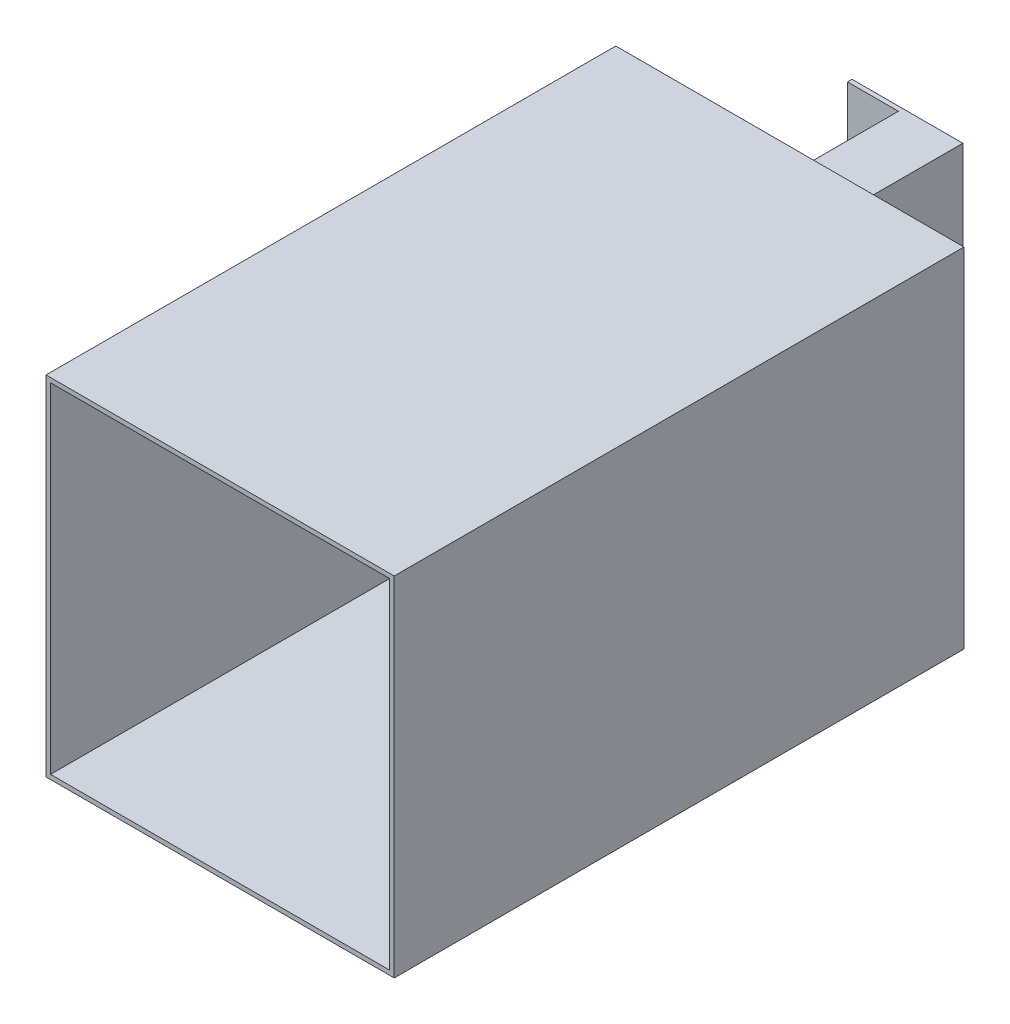
SolidWorks part; units mm, degrees
material "Cast Alloy Steel"
ref_plane "Front Plane" through (0, 0, 0) normal (0, 0, 1) x (1, 0, 0)
ref_plane "Top Plane" through (0, 0, 0) normal (0, 1, 0) x (1, 0, 0)
ref_plane "Right Plane" through (0, 0, 0) normal (1, 0, 0) x (0, 0, -1)
sketch "Sketch1" plane through (0, 0, 0) normal (0, 0, 1) x (1, 0, 0)
  line L0 (-77, 77) -> (77, 77)
  line L1 (-75, 75) -> (75, 75)
  line L2 (-75, 75) -> (-75, -75)
  line L3 (-75, -75) -> (75, -75)
  line L4 (75, 75) -> (75, -75)
  line L5 (-75, 75) -> (75, -75) construction
  line L6 (-75, -75) -> (75, 75) construction
  line L7 (77, 77) -> (77, -77)
  line L8 (-77, -77) -> (77, -77)
  line L9 (-77, 77) -> (-77, -77)
  point P0 (0, 0)
  dimension "D1" = 150
  dimension "D2" = 2
extrude "Boss-Extrude1" add sketch "Sketch1" along normal blind 250
sketch "Sketch2" plane through (0, 0, 0) normal (0, 0, -1) x (-1, 0, 0)
  line L0 (0, 75) -> (0, -75) construction
  line L1 (-77, 77) -> (77, 77)
  line L2 (-77, 77) -> (-77, -77)
  line L3 (-77, -77) -> (77, -77)
  line L4 (77, 77) -> (77, -77)
  line L5 (-75, 75) -> (75, 75) construction
  line L6 (75, -75) -> (-75, -75) construction
  circle A0 centre (0, 40) radius 20
  circle A1 centre (0, 0) radius 4
  dimension "D1" = 40
  dimension "D3" = 8
  dimension "D2" = 35
extrude "Boss-Extrude2" add sketch "Sketch2" along normal blind 2
sketch "Sketch3" plane through (0, 0, -2) normal (0, 0, -1) x (-1, 0, 0)
  line L0 (2, 64.5) -> (2, 62.5)
  line L1 (2, 62.5) -> (0, 62.5)
  line L2 (-22.5, 62.5) -> (-22.5, 17.5)
  line L3 (-22.5, 17.5) -> (22.5, 17.5) construction
  line L4 (22.5, 62.5) -> (22.5, 17.5) construction
  line L7 (-22.5, 62.5) -> (0, 62.5)
  line L8 (-22.5, 17.5) -> (0, 17.5)
  line L10 (-24.5, 15.5) -> (2, 15.5)
  line L11 (-24.5, 64.5) -> (-24.5, 15.5)
  line L12 (-24.5, 64.5) -> (2, 64.5)
  line L14 (2, 64.5) -> (2, 15.5) construction
  line L15 (0, 62.5) -> (0, 17.5) construction
  line L18 (0, 17.5) -> (2, 17.5)
  line L19 (2, 17.5) -> (2, 15.5)
  point P0 (0, 40)
  dimension "D1" = 45
  dimension "D2" = 2
extrude "Boss-Extrude3" add sketch "Sketch3" along normal blind 50
sketch "Sketch4" plane through (0, 0, -52) normal (0, 0, -1) x (-1, 0, 0)
  line L1 (-24.5, 64.5) -> (24.5, 64.5)
  line L2 (-24.5, 64.5) -> (-24.5, 15.5)
  line L3 (-24.5, 15.5) -> (24.5, 15.5)
  line L4 (24.5, 64.5) -> (24.5, 15.5)
  dimension "D1" = 49
  dimension "D2" = 49
extrude "Boss-Extrude4" add sketch "Sketch4" along normal blind 2
sketch "Sketch5" plane through (24.5, 0, 0) normal (1, 0, 0) x (0, 0, -1)
  line L0 (2, 17.5) -> (6, 17.5)
  line L2 (2, 62.5) -> (2, 17.5)
  line L3 (2, 62.5) -> (6, 62.5)
  line L4 (6, 62.5) -> (6, 17.5)
extrude "Cut-Extrude1" cut sketch "Sketch5" against normal blind 2
sketch "Sketch6" plane through (24.5, 0, 0) normal (1, 0, 0) x (0, 0, -1)
  line L1 (54, 40) -> (11.6739, 40) construction
  line L2 (54, 64.5) -> (54, 15.5) construction
  circle A0 centre (32, 40) radius 4
  dimension "D1" = 8
  dimension "D2" = 22
extrude "Cut-Extrude2" cut sketch "Sketch6" against normal blind 70
sketch "Sketch9" plane through (0, 0, 0) normal (0, 0, 1) x (1, 0, 0)
  circle A0 centre (0, 0) radius 74
  circle A1 centre (0, 0) radius 72
  dimension "D1" = 148
  dimension "D2" = 2
extrude "Boss-Extrude9" add sketch "Sketch9" along normal blind 50
sketch "Sketch10" plane through (0, 0, 50) normal (0, 0, 1) x (1, 0, 0)
  circle A0 centre (0, 0) radius 74
ref_plane "Plane1" through (0, 0, 80) normal (0, 0, 1) x (1, 0, 0)
sketch "Sketch12" plane through (0, 0, 80) normal (0, 0, 1) x (1, 0, 0)
  line L1 (-75, 75) -> (75, 75)
  line L2 (-75, 75) -> (-75, -75)
  line L3 (-75, -75) -> (75, -75)
  line L4 (75, 75) -> (75, -75)
sketch "Sketch13" plane through (0, 0, 0) normal (0, 1, 0) x (1, 0, 0)
  line L0 (74, -50) -> (75, -80)
  line L1 (-74, -50) -> (74, -50) construction
  line L2 (-74, -50) -> (74, -50) construction
  line L3 (75, -250) -> (75, 0) construction
  line L4 (-75, -80) -> (75, -80) construction
surface "Surface-Loft1"
